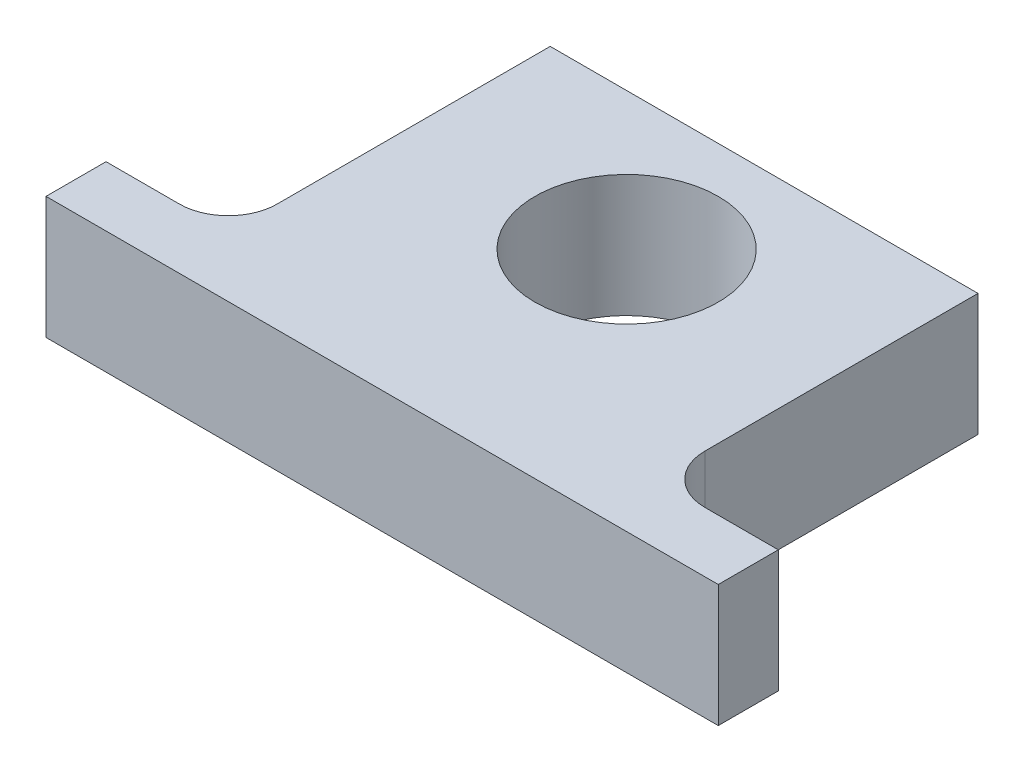
SolidWorks part; units mm, degrees
ref_plane "Front Plane" through (0, 0, 0) normal (0, 0, 1) x (1, 0, 0)
ref_plane "Top Plane" through (0, 0, 0) normal (0, 1, 0) x (1, 0, 0)
ref_plane "Right Plane" through (0, 0, 0) normal (1, 0, 0) x (0, 0, -1)
sketch "Sketch1" plane through (0, 0, 0) normal (0, 1, 0) x (1, 0, 0)
  line L0 (22.225, -8.5256) -> (22.225, 19.8438)
  line L1 (-22.225, 19.8438) -> (22.225, 19.8438)
  line L2 (-34.925, -13.6056) -> (-34.925, -19.8438)
  line L3 (-34.925, -19.8438) -> (34.925, -19.8438)
  line L4 (34.925, -13.6056) -> (34.925, -19.8438)
  line L7 (-22.225, 19.8438) -> (-22.225, -8.5256)
  line L8 (-34.925, -13.6056) -> (-27.305, -13.6056)
  line L9 (27.305, -13.6056) -> (34.925, -13.6056)
  arc A0 (27.305, -13.6056) -> (22.225, -8.5256) centre (27.305, -8.5256) cw
  arc A1 (-27.305, -13.6056) -> (-22.225, -8.5256) centre (-27.305, -8.5256) ccw
  circle A2 centre (0, 5.5562) radius 9.525
  point P0 (0, 0)
  dimension "D1" = 5.08
  dimension "D2" = 25.4
  dimension "D3" = 12.7
  dimension "D4" = 12.7
  dimension "D5" = 6.2382
  dimension "D6" = 69.85
  dimension "D7" = 39.6875
extrude "Boss-Extrude1" add sketch "Sketch1" along normal blind 12.7
